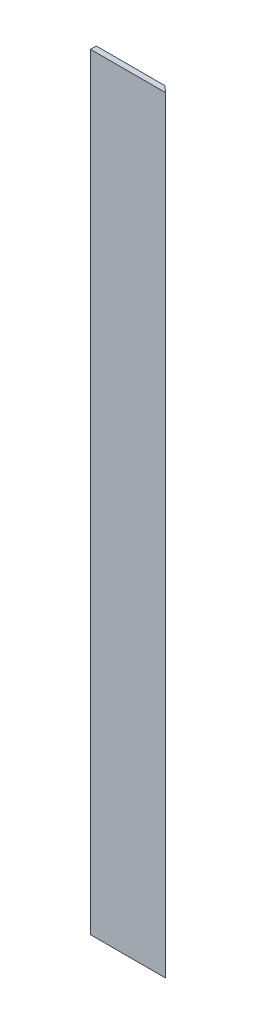
SolidWorks part; units mm, degrees
ref_plane "Спереди" through (0, 0, 0) normal (0, 0, 1) x (1, 0, 0)
ref_plane "Сверху" through (0, 0, 0) normal (0, 1, 0) x (1, 0, 0)
ref_plane "Справа" through (0, 0, 0) normal (1, 0, 0) x (0, 0, -1)
sketch "Эскиз1" plane through (0, 0, 0) normal (0, 1, 0) x (1, 0, 0)
  line L1 (0, -1) -> (47.762, -1)
  line L2 (0, -1) -> (0, -5)
  line L3 (0, -5) -> (52.1029, -5)
  line L4 (47.762, -1) -> (52.1029, -5)
  dimension "D1" = 4
extrude "Вытянуть1" add sketch "Эскиз1" along normal blind 533
